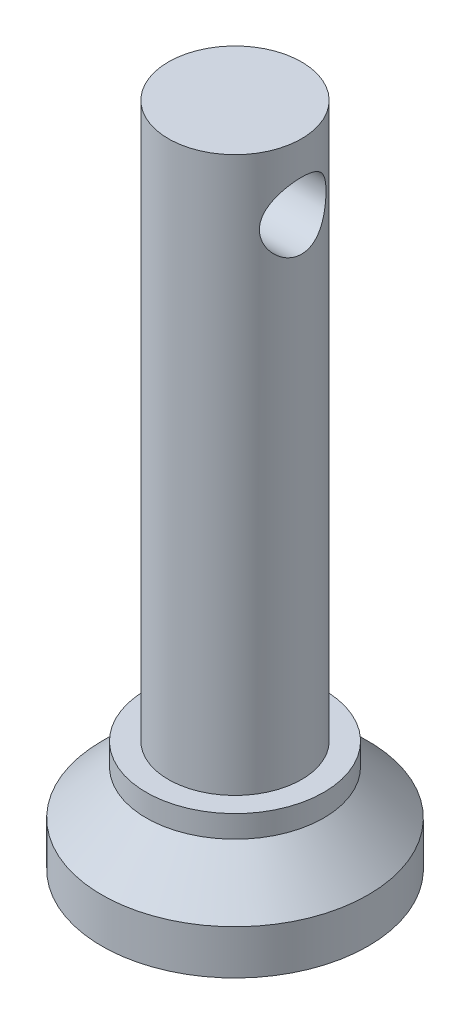
SolidWorks part; units mm, degrees
ref_plane "Front Plane" through (0, 0, 0) normal (0, 0, 1) x (1, 0, 0)
ref_plane "Top Plane" through (0, 0, 0) normal (0, 1, 0) x (1, 0, 0)
ref_plane "Right Plane" through (0, 0, 0) normal (1, 0, 0) x (0, 0, -1)
sketch "Sketch2" plane through (0, 0, 0) normal (0, 0, 1) x (1, 0, 0)
  line L0 (0, 0) -> (-6, 0)
  line L1 (-6, 0) -> (-6, 2)
  line L2 (-6, 2) -> (-4, 4)
  line L3 (-4, 4) -> (-4, 5)
  line L4 (-4, 5) -> (-3, 5)
  line L5 (-3, 30) -> (0, 30)
  line L6 (0, 30) -> (0, 0)
  line L7 (-3, 5) -> (-3, 30)
  dimension "D1" = 2
  dimension "D2" = 4
  dimension "D3" = 6
  dimension "D4" = 45
  dimension "D5" = 3
  dimension "D6" = 30
  dimension "D7" = 5
revolve "Revolve2" add sketch "Sketch2" angle 360 about L6
sketch "Sketch3" plane through (0, 0, 0) normal (1, 0, 0) x (0, 0, -1)
  line L0 (3, 30) -> (-3, 30) construction
  line L1 (0, 27) -> (0, 30) construction
  circle A0 centre (0, 27) radius 1.5
  dimension "D1" = 3
  dimension "D2" = 3
extrude "Cut-Extrude1" cut sketch "Sketch3" against normal through all and the other way through all
